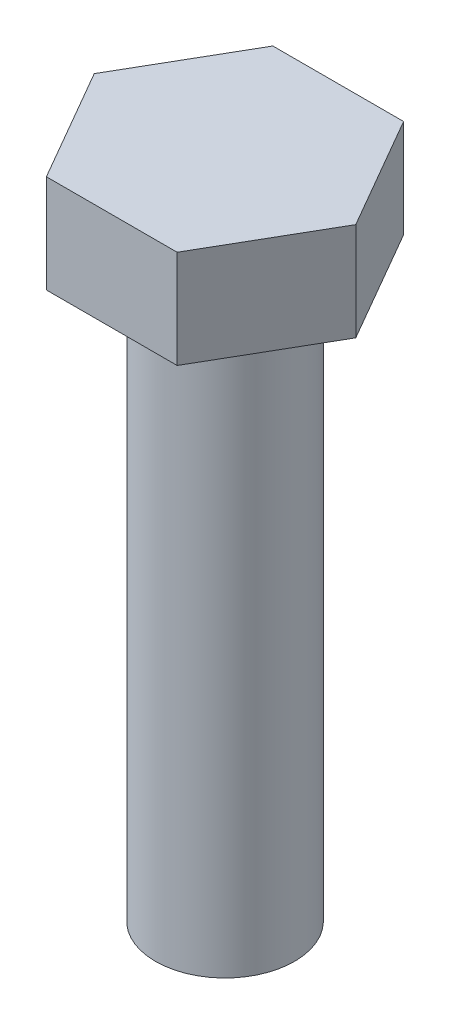
SolidWorks part; units mm, degrees
material "Plain Carbon Steel"
ref_plane "Front Plane" through (0, 0, 0) normal (0, 0, 1) x (1, 0, 0)
ref_plane "Top Plane" through (0, 0, 0) normal (0, 1, 0) x (1, 0, 0)
ref_plane "Right Plane" through (0, 0, 0) normal (1, 0, 0) x (0, 0, -1)
sketch "Sketch1" plane through (0, 0, 0) normal (0, 1, 0) x (1, 0, 0)
  line L0 (7.3323, 0) -> (3.6662, 6.35)
  line L1 (3.6662, 6.35) -> (-3.6662, 6.35)
  line L2 (-3.6662, 6.35) -> (-7.3323, 0)
  line L3 (-7.3323, 0) -> (-3.6662, -6.35)
  line L4 (-3.6662, -6.35) -> (3.6662, -6.35)
  line L5 (3.6662, -6.35) -> (7.3323, 0)
  dimension "D1" = 7.3323
  dimension "D2" = 3.6662
  dimension "D3" = 6.35
  dimension "D4" = 7.3323
  dimension "D5" = 3.6662
  dimension "D6" = 6.35
  dimension "D7" = 3.6662
  dimension "D8" = 6.35
  dimension "D9" = 7.3323
extrude "Boss-Extrude1" add sketch "Sketch1" along normal blind 5.5 from offset 0
sketch "Sketch2" plane through (0, 0, 0) normal (0, 1, 0) x (1, 0, 0)
  circle A0 centre (0, 0) radius 3.9
  dimension "D1" = 7.8
extrude "Boss-Extrude2" add sketch "Sketch2" along normal blind 32 from offset 32
